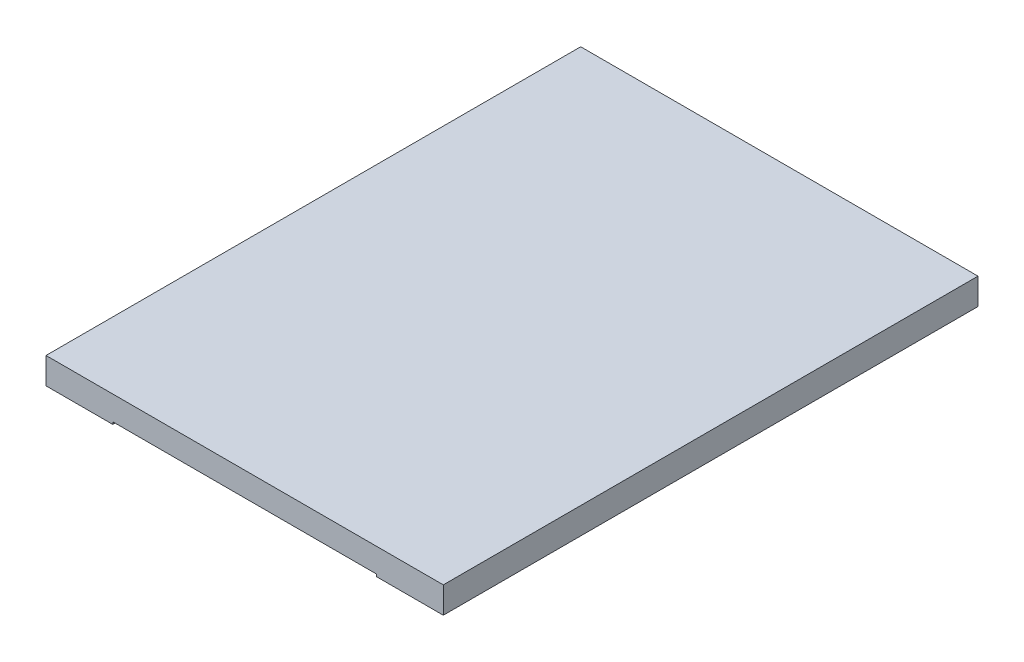
SolidWorks part; units mm, degrees
ref_plane "Спереди" through (0, 0, 0) normal (0, 0, 1) x (1, 0, 0)
ref_plane "Сверху" through (0, 0, 0) normal (0, 1, 0) x (1, 0, 0)
ref_plane "Справа" through (0, 0, 0) normal (1, 0, 0) x (0, 0, -1)
sketch "Эскиз1" plane through (0, 0, 0) normal (0, 1, 0) x (1, 0, 0)
  line L1 (-17.35, -23.35) -> (17.35, -23.35)
  line L2 (-17.35, -23.35) -> (-17.35, 23.35)
  line L3 (-17.35, 23.35) -> (17.35, 23.35)
  line L4 (17.35, -23.35) -> (17.35, 23.35)
  line L5 (-17.35, -23.35) -> (17.35, 23.35) construction
  line L6 (-17.35, 23.35) -> (17.35, -23.35) construction
  point P0 (0, 0)
extrude "Бобышка-Вытянуть1" add sketch "Эскиз1" along normal blind 2.3
sketch "Эскиз2" plane through (0, 0, 0) normal (0, -1, 0) x (1, 0, 0)
  line L0 (0, 0) -> (0, -2.75) construction
  line L6 (17.35, -23.35) -> (-17.35, -23.35) construction
  line L7 (14.015, 14.77) -> (-14.015, 14.77)
  line L8 (14.015, 14.77) -> (14.015, -20.27)
  line L14 (14.015, -20.27) -> (-14.015, -20.27)
  line L15 (-14.015, 14.77) -> (-14.015, -20.27)
  line L20 (14.015, 14.77) -> (-14.015, -20.27) construction
  line L21 (14.015, -20.27) -> (-14.015, 14.77) construction
  line L31 (15.915, 16.44) -> (-15.915, 16.44)
  line L32 (15.915, 16.44) -> (15.915, -21.94)
  line L33 (15.915, -21.94) -> (-15.915, -21.94)
  line L34 (-15.915, 16.44) -> (-15.915, -21.94)
  line L35 (15.915, 16.44) -> (-15.915, -21.94) construction
  line L36 (15.915, -21.94) -> (-15.915, 16.44) construction
  dimension "D1" = 35.04
  dimension "D2" = 28.03
  dimension "D3" = 3.08
  dimension "D4" = 31.83
  dimension "D5" = 1.41
extrude "Вырез-Вытянуть1" cut sketch "Эскиз2" against normal blind 0.2
sketch "Эскиз3" plane through (0, 0, 0) normal (0, -1, 0) x (1, 0, 0)
  line L0 (15.915, 16.44) -> (-15.915, 16.44)
  line L1 (-15.915, 16.44) -> (-15.915, 20.6571)
  line L7 (-15.915, 20.6571) -> (15.915, 20.6571)
  line L8 (15.915, 20.6571) -> (15.915, 16.44)
  point P4 (-16.1031, 20.6571)
extrude "Вырез-Вытянуть2" cut sketch "Эскиз3" against normal blind 0.5
sketch "Эскиз4" plane through (0, 0, 0) normal (0, -1, 0) x (1, 0, 0)
  line L0 (15.915, 20.6571) -> (-15.915, 20.6571) construction
  line L1 (11.515, 23.35) -> (-11.515, 23.35)
  line L2 (11.515, 23.35) -> (11.515, 17.9643) construction
  line L3 (11.515, 17.9643) -> (-11.515, 17.9643) construction
  line L4 (-11.515, 23.35) -> (-11.515, 17.9643) construction
  line L5 (11.515, 23.35) -> (-11.515, 17.9643) construction
  line L6 (11.515, 17.9643) -> (-11.515, 23.35) construction
  line L7 (-17.35, 23.35) -> (17.35, 23.35) construction
  line L8 (11.515, 23.35) -> (11.515, 20.6571)
  line L9 (11.515, 20.6571) -> (-11.515, 20.6571)
  line L10 (-11.515, 20.6571) -> (-11.515, 23.35)
  point P0 (0, 20.6571)
  dimension "D1" = 0
  dimension "D2" = 4.4
extrude "Вырез-Вытянуть3" cut sketch "Эскиз4" against normal blind 0.2
